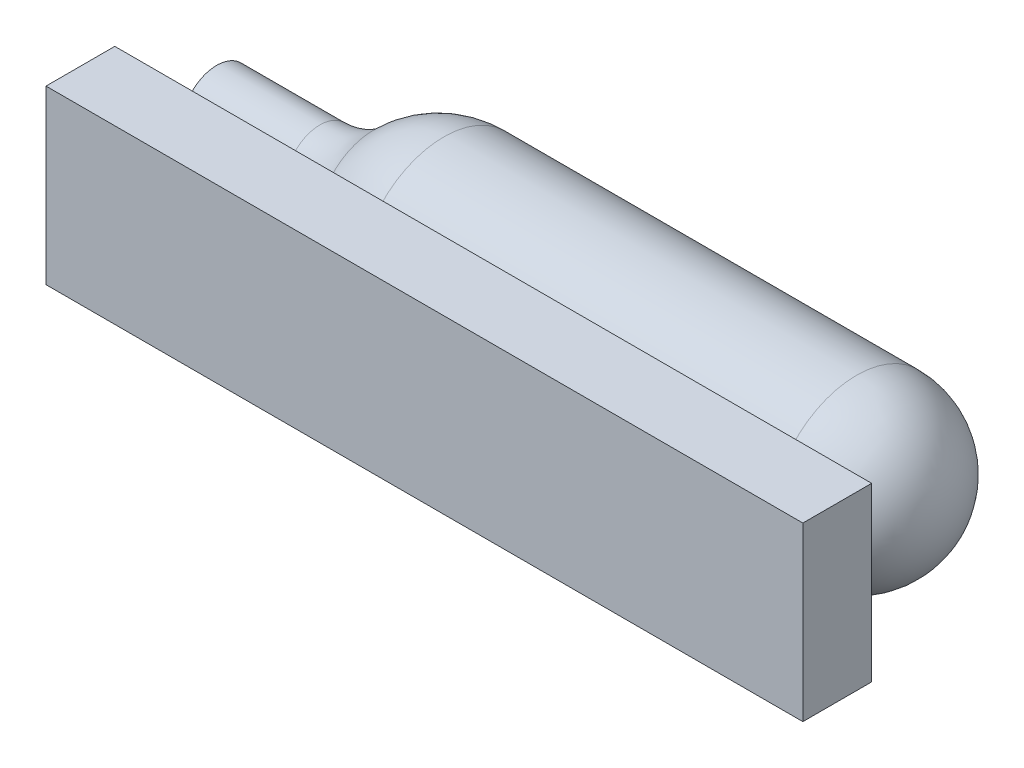
SolidWorks part; units mm, degrees
ref_plane "Front Plane" through (0, 0, 0) normal (0, 0, 1) x (1, 0, 0)
ref_plane "Top Plane" through (0, 0, 0) normal (0, 1, 0) x (1, 0, 0)
ref_plane "Right Plane" through (0, 0, 0) normal (1, 0, 0) x (0, 0, -1)
sketch "Sketch1" plane through (0, 0, 0) normal (0, 0, 1) x (1, 0, 0)
  line L0 (-126.2267, -6.8203) -> (-164.3267, -6.8203)
  line L1 (-80.4825, 12.2297) -> (71.9175, 12.2297)
  line L5 (-164.3267, -6.8203) -> (-164.3267, -19.5203)
  line L6 (-164.3267, -19.5203) -> (103.6675, -19.5203)
  arc A0 (71.9175, 12.2297) -> (103.6675, -19.5203) centre (71.9175, -19.5203) cw
  arc A1 (-80.4825, 12.2297) -> (-106.395, 1.4385) centre (-80.4825, -24.2774) ccw
  arc A2 (-106.395, 1.4385) -> (-126.2267, -6.8203) centre (-126.2267, 21.1198) cw
  dimension "D4" = 36.507
  dimension "D6" = 31.75
  dimension "D2" = 31.75
  dimension "D1" = 152.4
  dimension "D3" = 38.1
  dimension "D5" = 12.7
revolve "Revolve2" add sketch "Sketch1" angle 360 about L6
ref_plane "Plane1" through (0, 0, 31.75) normal (0, 0, 1) x (1, 0, 0)
sketch "Sketch2" plane through (0, 0, 31.75) normal (0, 0, 1) x (1, 0, 0)
  line L1 (-170.18, -51.308) -> (109.22, -51.308)
  line L2 (-170.18, -51.308) -> (-170.18, 12.192)
  line L3 (-170.18, 12.192) -> (109.22, 12.192)
  line L4 (109.22, -51.308) -> (109.22, 12.192)
  point P4 (-170.0378, 12.192)
  point P6 (-170.18, -19.558)
  dimension "D1" = 63.5
  dimension "D2" = 19.558
  dimension "D3" = 279.4
  dimension "D4" = 170.18
extrude "Boss-Extrude1" add sketch "Sketch2" along normal blind 25.4 separate body
